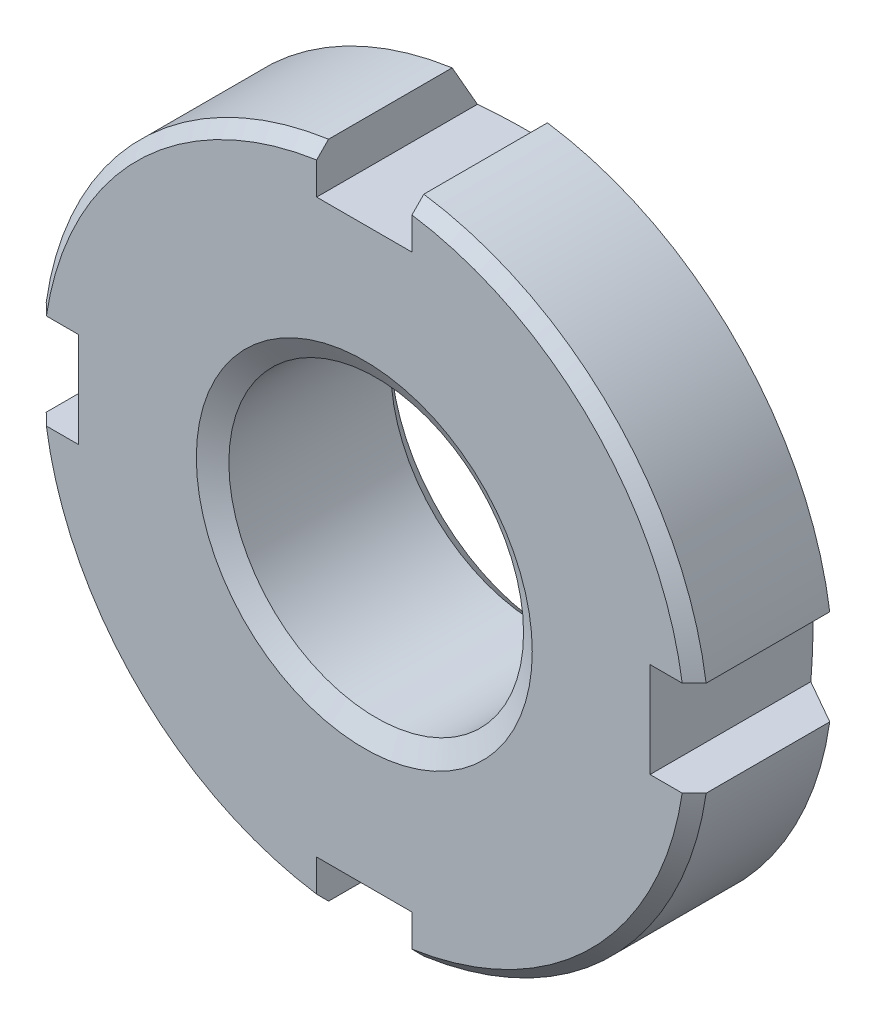
SolidWorks part; units mm, degrees
ref_plane "Front" through (0, 0, 0) normal (0, 0, 1) x (1, 0, 0)
ref_plane "Top" through (0, 0, 0) normal (0, 1, 0) x (1, 0, 0)
ref_plane "Right" through (0, 0, 0) normal (1, 0, 0) x (0, 0, -1)
other "Configuration Table"
sketch "Sketch1" plane through (0, 0, 0) normal (0, 0, 1) x (1, 0, 0)
  circle A0 centre (0, 0) radius 14
  circle A1 centre (0, 0) radius 6.188
  dimension "dk" = 28
  dimension "D" = 12.376
extrude "BaseNut" add sketch "Sketch1" against normal blind 8
cosmetic thread "ThreadCosmetic1" [suppressed] parameters "D2"=14
sketch "Sketch2" plane through (0, 0, 0) normal (0, 1, 0) x (1, 0, 0)
  line L0 (-14, 8) -> (-10, 8)
  line L2 (-10, 8) -> (-14, 5.6906)
  line L3 (-14, 5.6906) -> (-14, 8)
  line L4 (0, 4.5605) -> (0, -11.63) construction
  line L7 (14, 8) -> (-14, 8) construction
  line L8 (-14, 8) -> (-14, 0) construction
  dimension "d1" = 20
  dimension "Angle" = 30
revolve "StepCut" cut sketch "Sketch2" angle 360 about L4
chamfer "Chamfer1" distance 0.5 angle 45 1 edges at (14, 0, 0)
chamfer "EndChamfer" distance 0.5 angle 60 1 edges at (6.188, 0, 0)
chamfer "Chamfer2" distance 0.7 angle 45 1 edges at (6.188, 0, -8)
sketch "Sketch3" plane through (-3.5543, 4.131, -8) normal (0, 0, -1) x (-1, 0, 0)
  line L0 (-5.5543, -16.131) -> (-1.5543, -16.131)
  line L1 (-1.5543, -16.131) -> (-1.5543, -17.9874)
  line L3 (-5.5543, -17.9874) -> (-5.5543, -16.131)
  circle A0 centre (-3.5543, -4.131) radius 14 construction
  arc A1 (-5.5543, -17.9874) -> (-1.5543, -17.9874) centre (-3.5543, -4.131) ccw
  dimension "n1" = 2
  dimension "n" = 4
  dimension "t" = 2
extrude "SlotCut" cut sketch "Sketch3" against normal through all
pattern_circular "SlotPat" count 4 over 360 about axis through (0, 0, -4.5605) along (0, 0, 1) of "SlotCut"
sketch "Sketch4" plane through (0, 0, 0) normal (1, 0, 0) x (0, 0, -1)
  line L0 (16.8557, 0) -> (-7.8489, 0) construction
  line L1 (6.894, 5.376) -> (7.706, 5.376)
  line L2 (7.706, 5.376) -> (7.706, 6.188)
  line L3 (7.706, 6.188) -> (7.3, 6.8912)
  line L4 (7.3, 6.8912) -> (6.894, 6.188)
  line L5 (6.894, 6.188) -> (6.894, 5.376)
  line L6 (7.3, -6.188) -> (7.3, 6.188) construction
  dimension "D1" = 0.812
  dimension "D2" = 12.376
revolve "Cut-Revolve10" [suppressed] cut sketch "Sketch4" angle 360 about L0
pattern_linear "LPattern10" [suppressed] count 8 spacing 0.9744 along (0, 0, 1)
equation "\"n1@Sketch3\" = \"n@Sketch3\" / 2"
equation "\"D1@Chamfer2\" = \"C1@EndChamfer\" * 1.4"
equation "\"D1@Sketch4\" = (  \"D2@ThreadCosmetic1\" - \"D@Sketch1\" )  / 2"
equation "\"D2@Sketch4\" = \"D@Sketch1\""
equation "\"D3@LPattern10\" = \"D1@Sketch4\" * 1.2"
equation "\"D1@LPattern10\" = \"m@BaseNut\" / \"D3@LPattern10\""
